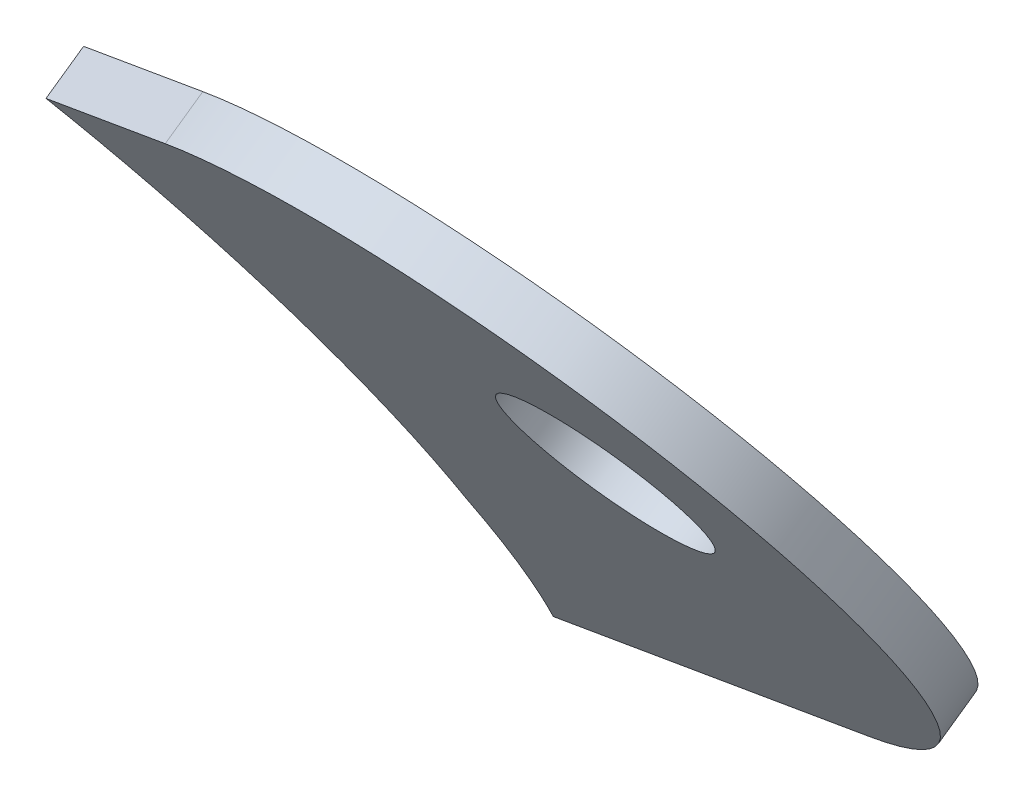
SolidWorks part; units mm, degrees
ref_plane "Front Plane" through (0, 0, 0) normal (0, 0, 1) x (1, 0, 0)
ref_plane "Top Plane" through (0, 0, 0) normal (0, 1, 0) x (1, 0, 0)
ref_plane "Right Plane" through (0, 0, 0) normal (1, 0, 0) x (0, 0, -1)
ref_plane "Plane1" through (0, 229.6997, -328.0452) normal (0, -0.5736, 0.8192) x (1, 0, 0)
sketch "Sketch1" plane through (0, 229.6997, -328.0452) normal (0, -0.5736, 0.8192) x (1, 0, 0)
  line L0 (356.2999, 70.5516) -> (376.9254, 80.822)
  line L1 (365.6036, 103.5591) -> (344.9781, 93.2888)
  line L2 (344.9781, 93.2888) -> (356.2999, 70.5516)
  line L3 (371.2645, 92.1906) -> (375.5277, 94.3134) construction
  arc A0 (376.9254, 80.822) -> (365.6036, 103.5591) centre (371.2645, 92.1906) ccw
  circle A1 centre (375.5277, 94.3134) radius 3.302
  point P4 (350.639, 81.9202)
  dimension "D1" = 4.7625
  dimension "D2" = 25.4
extrude "Boss-Extrude1" add sketch "Sketch1" along normal blind 1.5875
ref_plane "Plane2" through (364.3517, 343.6254, -135.3997) normal (-0.0893, -0.3048, -0.9482) x (-0.996, 0.0273, 0.085)
sketch "Sketch2" plane through (364.3517, 343.6254, -135.3997) normal (-0.0893, -0.3048, -0.9482) x (-0.996, 0.0273, 0.085)
  circle A0 centre (0, 0) radius 12.7
  dimension "D1" = 25.4
extrude "Cut-Extrude1" cut sketch "Sketch2" along normal through all
sketch "Sketch3" plane through (0, 228.7892, -326.7448) normal (0, -0.5736, 0.8192) x (1, 0, 0)
  line L0 (359.8287, 100.6835) -> (358.4382, 99.9911)
  line L1 (358.4382, 99.9911) -> (360.8703, 72.8274)
  ellipse E0 centre (350.8744, 84.0131) end of major axis (353.2331, 104.9802) minor radius 12.7 (360.8703, 72.8274) -> (359.8287, 100.6835) ccw construction
  ellipse E1 centre (350.8744, 84.0131) end of major axis (353.2331, 104.9802) minor radius 12.7 (360.8703, 72.8274) -> (359.8287, 100.6835) ccw
extrude "Cut-Extrude2" cut sketch "Sketch3" against normal through all
sketch "Sketch4" plane through (0, 229.6997, -328.0452) normal (0, 0.5736, -0.8192) x (-1, 0, 0)
  line L0 (-361.6175, 73.1995) -> (-360.8703, 72.8274)
  line L1 (-360.8703, 72.8274) -> (-363.3614, 81.5487)
  ellipse E0 centre (-350.639, 81.9202) end of major axis (-352.9976, 102.8873) minor radius 12.7 (-363.3614, 81.5487) -> (-361.6175, 73.1995) ccw construction
  ellipse E1 centre (-350.639, 81.9202) end of major axis (-352.9976, 102.8873) minor radius 12.7 (-363.3614, 81.5487) -> (-361.6175, 73.1995) ccw
extrude "Cut-Extrude3" cut sketch "Sketch4" against normal through all
